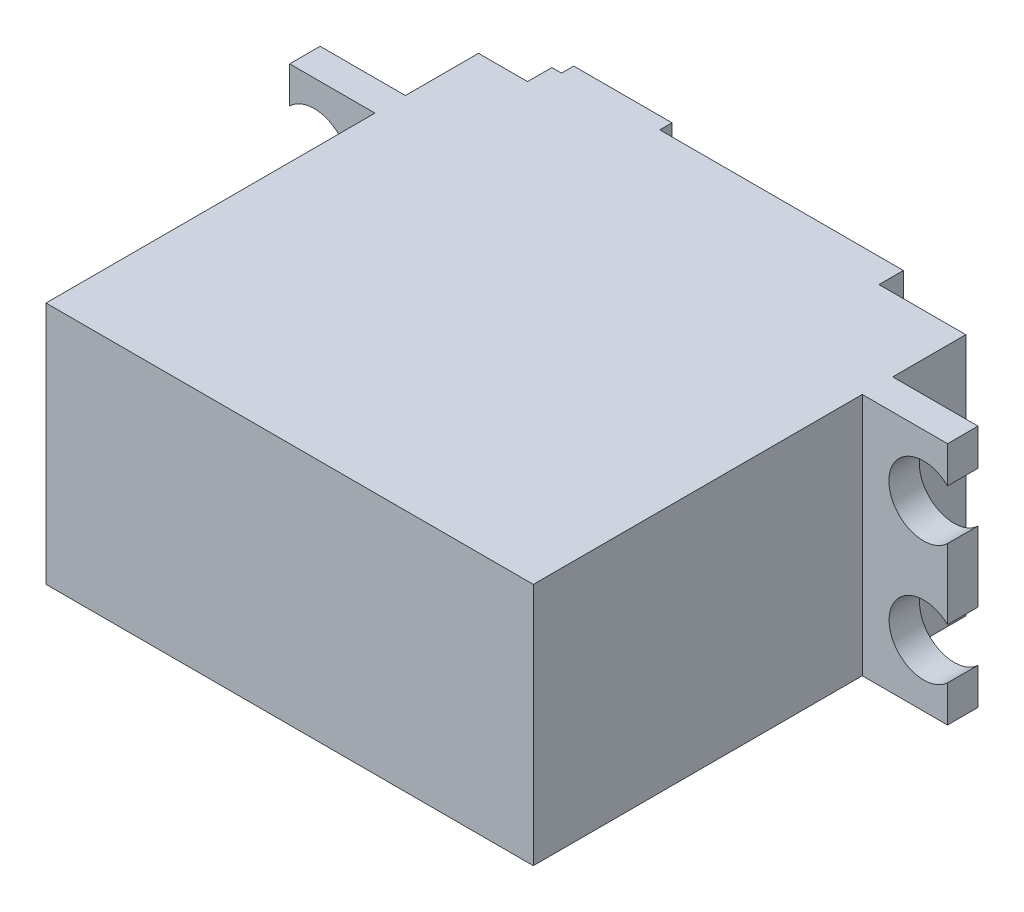
SolidWorks part; units mm, degrees
ref_plane "Front Plane" through (0, 0, 0) normal (0, 0, 1) x (1, 0, 0)
ref_plane "Top Plane" through (0, 0, 0) normal (0, 1, 0) x (1, 0, 0)
ref_plane "Right Plane" through (0, 0, 0) normal (1, 0, 0) x (0, 0, -1)
sketch "Sketch1" plane through (0, 0, 0) normal (0, 1, 0) x (1, 0, 0)
  line L0 (-59.2456, 22.9329) -> (-63.2688, 22.9329)
  line L1 (-63.2688, 22.9329) -> (-63.2688, 16.9329)
  line L2 (-63.2688, 16.9329) -> (-70.2688, 16.9329)
  line L3 (-70.2688, 16.9329) -> (-70.2688, 14.4329)
  line L4 (-70.2688, 14.4329) -> (-63.2688, 14.4329)
  line L5 (-63.2688, 14.4329) -> (-63.2688, -12.5671)
  line L6 (-63.2688, -12.5671) -> (-23.2688, -12.5671)
  line L7 (-23.2688, -12.5671) -> (-23.2688, 14.4329)
  line L8 (-23.2688, 14.4329) -> (-16.2688, 14.4329)
  line L9 (-16.2688, 14.4329) -> (-16.2688, 16.9329)
  line L10 (-16.2688, 16.9329) -> (-23.2688, 16.9329)
  line L11 (-23.2688, 16.9329) -> (-23.2688, 22.9329)
  line L12 (-23.2688, 22.9329) -> (-30.3931, 22.9329)
  line L13 (-30.3931, 22.9329) -> (-30.3931, 24.9329)
  line L14 (-30.3931, 24.9329) -> (-50.386, 24.9329)
  line L15 (-50.386, 24.9329) -> (-50.386, 25.935)
  line L16 (-50.386, 25.935) -> (-54.386, 25.935)
  line L17 (-54.386, 25.935) -> (-54.386, 29.935)
  line L18 (-54.386, 29.935) -> (-57.386, 29.935)
  line L19 (-57.386, 29.935) -> (-57.386, 25.935)
  line L20 (-57.386, 25.935) -> (-58.4542, 25.935)
  line L21 (-58.4542, 25.935) -> (-58.4542, 24.9329)
  line L22 (-58.4542, 24.9329) -> (-59.2456, 24.9329)
  line L23 (-59.2456, 24.9329) -> (-59.2456, 22.9329)
extrude "Boss-Extrude1" add sketch "Sketch1" along normal blind 20
sketch "Sketch2" plane through (0, 0, -25.935) normal (0, 0, -1) x (-1, 0, 0)
  line L0 (54.274, 8.9278) -> (57.429, 8.9278)
  line L1 (57.429, 8.9278) -> (57.429, -0.7357)
  line L2 (57.429, -0.7357) -> (54.274, -0.7357)
  line L3 (54.274, -0.7357) -> (54.274, 8.9278)
extrude "Cut-Extrude1" cut sketch "Sketch2" along normal blind 4
sketch "Sketch3" plane through (0, 0, -29.935) normal (0, 0, -1) x (-1, 0, 0)
  line L0 (54.386, 20) -> (57.386, 20)
  line L1 (57.386, 20) -> (57.386, 13)
  line L3 (57.386, 13) -> (54.386, 13)
  line L5 (54.386, 13) -> (54.386, 20)
extrude "Cut-Extrude2" cut sketch "Sketch3" against normal blind 4
sketch "Sketch4" plane through (0, 0, -29.935) normal (0, 0, -1) x (-1, 0, 0)
  circle A0 centre (55.7952, 11.1021) radius 1.2814
extrude "Boss-Extrude3" add sketch "Sketch4" along normal blind 1
sketch "Sketch5" plane through (0, 0, -16.9329) normal (0, 0, -1) x (-1, 0, 0)
  line L1 (70.2688, 20) -> (70.2688, 0) construction
  arc A0 (70.2688, 17) -> (70.2688, 12.9772) centre (68.2574, 14.9886) ccw
  arc A1 (70.2688, 3) -> (70.2688, 7.004) centre (68.248, 5.002) cw
  line M2 (70.2688, 0) -> (70.2688, 20)
extrude "Cut-Extrude3" cut sketch "Sketch5" against normal through all and the other way through all contours A0 M2 | A1 M2
sketch "Sketch6" plane through (0, 0, -16.9329) normal (0, 0, -1) x (-1, 0, 0)
  line L0 (16.2688, 20) -> (16.2688, 17)
  line L1 (16.2688, 20) -> (16.2688, 0) construction
  line L2 (16.2688, 0) -> (16.2688, 3)
  arc A0 (16.2688, 3) -> (16.2688, 7.1342) centre (18.2229, 5.0671) ccw
  arc A1 (16.2688, 17) -> (16.2688, 12.8991) centre (18.2404, 14.9495) cw
  line M4 (16.2688, 20) -> (16.2688, 0)
extrude "Cut-Extrude4" cut sketch "Sketch6" against normal through all and the other way through all contours A1 M4 | A0 M4
